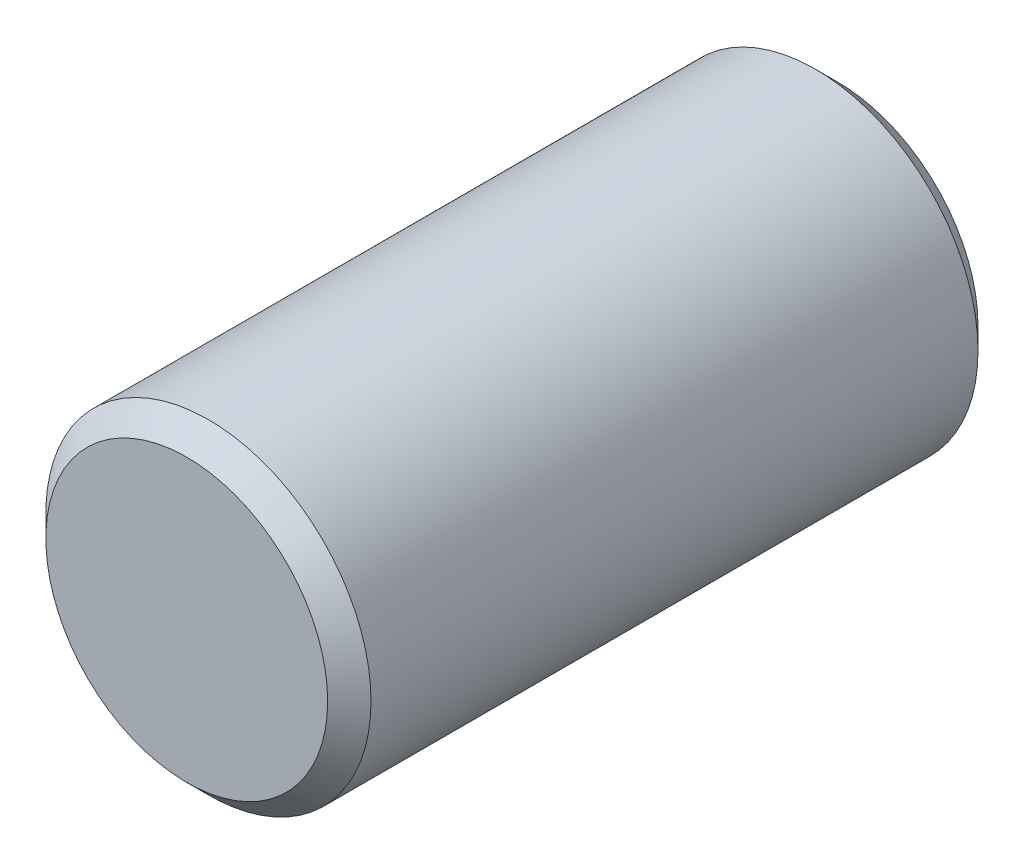
SolidWorks part; units mm, degrees
ref_plane "Front Plane" through (0, 0, 0) normal (0, 0, 1) x (1, 0, 0)
ref_plane "Top Plane" through (0, 0, 0) normal (0, 1, 0) x (1, 0, 0)
ref_plane "Right Plane" through (0, 0, 0) normal (1, 0, 0) x (0, 0, -1)
sketch "Sketch1" plane through (0, 0, 0) normal (0, 0, 1) x (1, 0, 0)
  circle A0 centre (0, 0) radius 0.75
  dimension "D1" = 1.5
extrude "Boss-Extrude1" add sketch "Sketch1" along normal mid plane 3 contours A0
chamfer "Chamfer1" distance 0.1 angle 45 2 edges at (0.75, 0, -1.5) (0.75, 0, 1.5)
